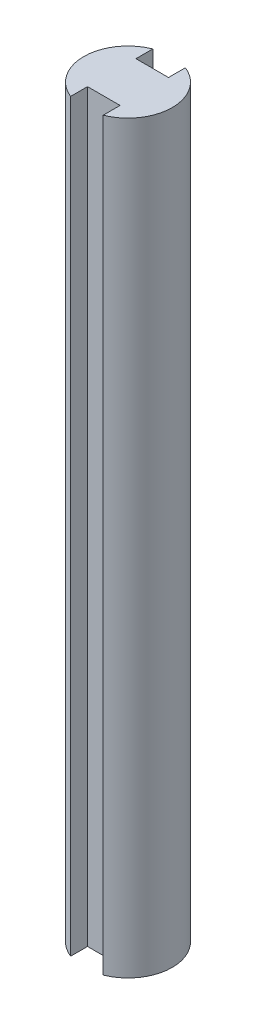
SolidWorks part; units mm, degrees
material "PVC Rigid"
ref_plane "Front Plane" through (0, 0, 0) normal (0, 0, 1) x (1, 0, 0)
ref_plane "Top Plane" through (0, 0, 0) normal (0, 1, 0) x (1, 0, 0)
ref_plane "Right Plane" through (0, 0, 0) normal (1, 0, 0) x (0, 0, -1)
sketch "Sketch1" plane through (0, 0, 0) normal (0, 1, 0) x (1, 0, 0)
  line L0 (-1.75, 4.4159) -> (-1.75, 2.6)
  line L1 (-1.75, 2.6) -> (1.75, 2.6)
  line L2 (1.75, 2.6) -> (1.75, 4.4159)
  line L3 (-1.75, -4.4159) -> (-1.75, -2.6)
  line L4 (-1.75, -2.6) -> (1.75, -2.6)
  line L5 (1.75, -2.6) -> (1.75, -4.4159)
  circle A0 centre (0, 0) radius 4.75
  dimension "D1" = 9.5
  dimension "D2" = 3.5
  dimension "D3" = 5.2
extrude "Boss-Extrude1" add sketch "Sketch1" along normal blind 80 contours L5 A0 L2 L1 L0 L3 L4
